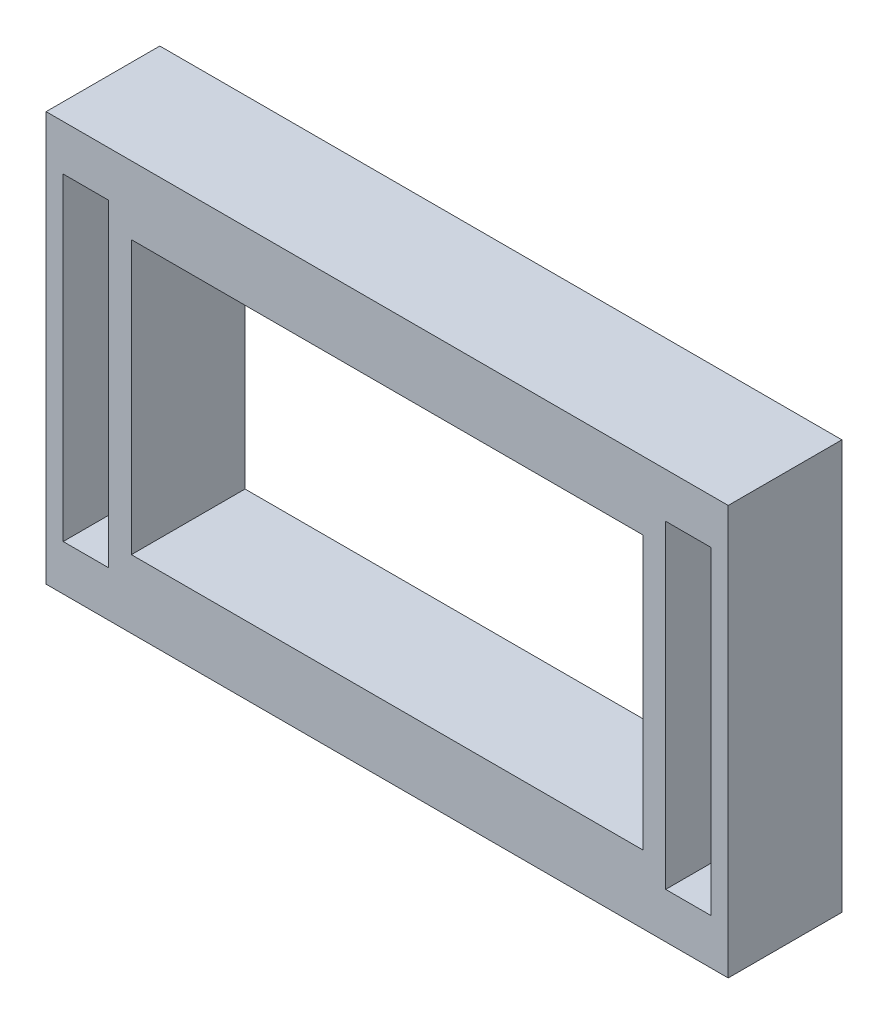
SolidWorks part; units mm, degrees
ref_plane "Front Plane" through (0, 0, 0) normal (0, 0, 1) x (1, 0, 0)
ref_plane "Top Plane" through (0, 0, 0) normal (0, 1, 0) x (1, 0, 0)
ref_plane "Right Plane" through (0, 0, 0) normal (1, 0, 0) x (0, 0, -1)
sketch "Sketch1" plane through (0, 0, 0) normal (0, 0, 1) x (1, 0, 0)
  line L1 (-11.25, 6) -> (11.25, 6)
  line L2 (-11.25, 6) -> (-11.25, -6)
  line L3 (-11.25, -6) -> (11.25, -6)
  line L4 (11.25, 6) -> (11.25, -6)
  line L5 (-11.25, 6) -> (11.25, -6) construction
  line L6 (-11.25, -6) -> (11.25, 6) construction
  line L7 (-15, 9) -> (15, 9)
  line L8 (-15, 9) -> (-15, -9)
  line L9 (-15, -9) -> (15, -9)
  line L10 (15, 9) -> (15, -9)
  line L11 (-15, 9) -> (15, -9) construction
  line L12 (-15, -9) -> (15, 9) construction
  point P0 (0, 0)
  point P5 (0, 0)
  dimension "D1" = 22.5
  dimension "D2" = 12
  dimension "D3" = 9
  dimension "D4" = 15
extrude "Boss-Extrude2" add sketch "Sketch1" along normal blind 5
sketch "Sketch2" plane through (0, 0, 5) normal (0, 0, 1) x (1, 0, 0)
  line L0 (15, 9) -> (-15, 9) construction
  line L1 (-14.25, 7) -> (-12.25, 7)
  line L2 (-14.25, 7) -> (-14.25, -7)
  line L3 (-14.25, -7) -> (-12.25, -7)
  line L4 (-12.25, 7) -> (-12.25, -7)
  line L5 (-14.25, 7) -> (-12.25, -7) construction
  line L6 (-14.25, -7) -> (-12.25, 7) construction
  line L7 (12.25, 7.0222) -> (14.25, 7.0222)
  line L8 (12.25, 7.0222) -> (12.25, -7)
  line L9 (12.25, -7) -> (14.25, -7)
  line L10 (14.25, 7.0222) -> (14.25, -7)
  line L11 (12.25, 7.0222) -> (14.25, -7) construction
  line L12 (12.25, -7) -> (14.25, 7.0222) construction
  line L13 (-15, -9) -> (15, -9) construction
  line L14 (11.25, -6) -> (11.25, 6) construction
  line L15 (-11.25, 6) -> (-11.25, -6) construction
  point P0 (-13.25, 0)
  point P5 (13.25, 0.0111)
  dimension "D1" = 2
  dimension "D2" = 2
  dimension "D3" = 2
  dimension "D4" = 2
  dimension "D5" = 1.9778
  dimension "D6" = 2
  dimension "D7" = 1
  dimension "D8" = 1
  dimension "D9" = 14
  dimension "D10" = 14.0222
extrude "Cut-Extrude1" cut sketch "Sketch2" against normal blind 4
